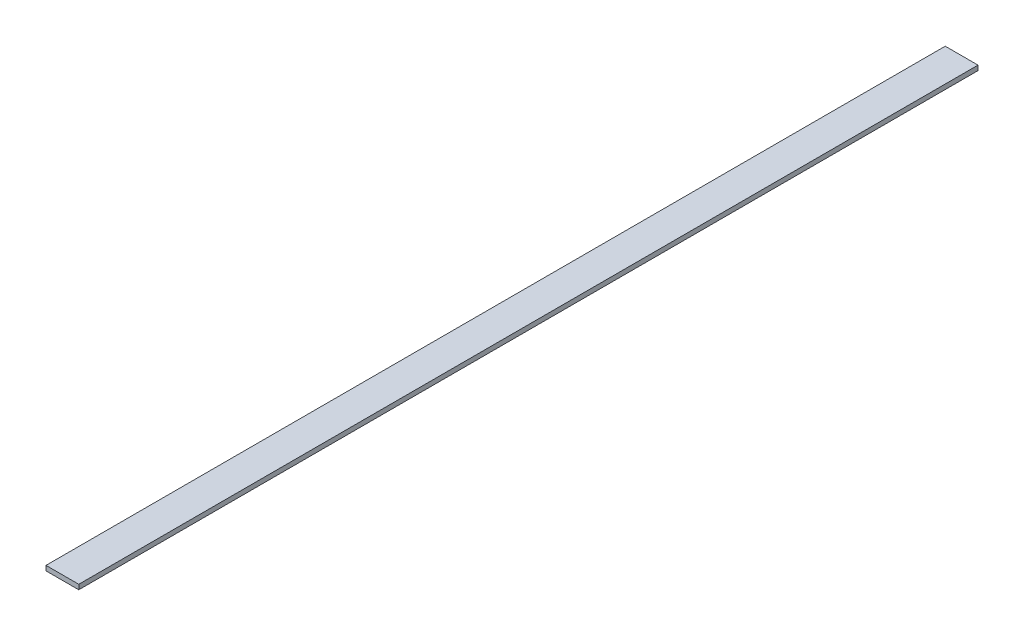
SolidWorks part; units mm, degrees
material "Manual Density from Real Component Bordo attacco e uscita"
ref_plane "Piano frontale" through (0, 0, 0) normal (0, 0, 1) x (1, 0, 0)
ref_plane "Piano superiore" through (0, 0, 0) normal (0, 1, 0) x (1, 0, 0)
ref_plane "Piano destro" through (0, 0, 0) normal (1, 0, 0) x (0, 0, -1)
sketch "Schizzo1" plane through (0, 0, 0) normal (0, 0, 1) x (1, 0, 0)
  line L1 (4.1, -0.6) -> (-4.1, -0.6)
  line L2 (4.1, -0.6) -> (4.1, 0.6)
  line L3 (4.1, 0.6) -> (-4.1, 0.6)
  line L4 (-4.1, -0.6) -> (-4.1, 0.6)
  line L5 (4.1, -0.6) -> (-4.1, 0.6) construction
  line L6 (4.1, 0.6) -> (-4.1, -0.6) construction
  point P0 (0, 0)
  dimension "D1" = 1.2
  dimension "D2" = 8.2
extrude "Estrusione-Estrusione1" add sketch "Schizzo1" along normal blind 225
